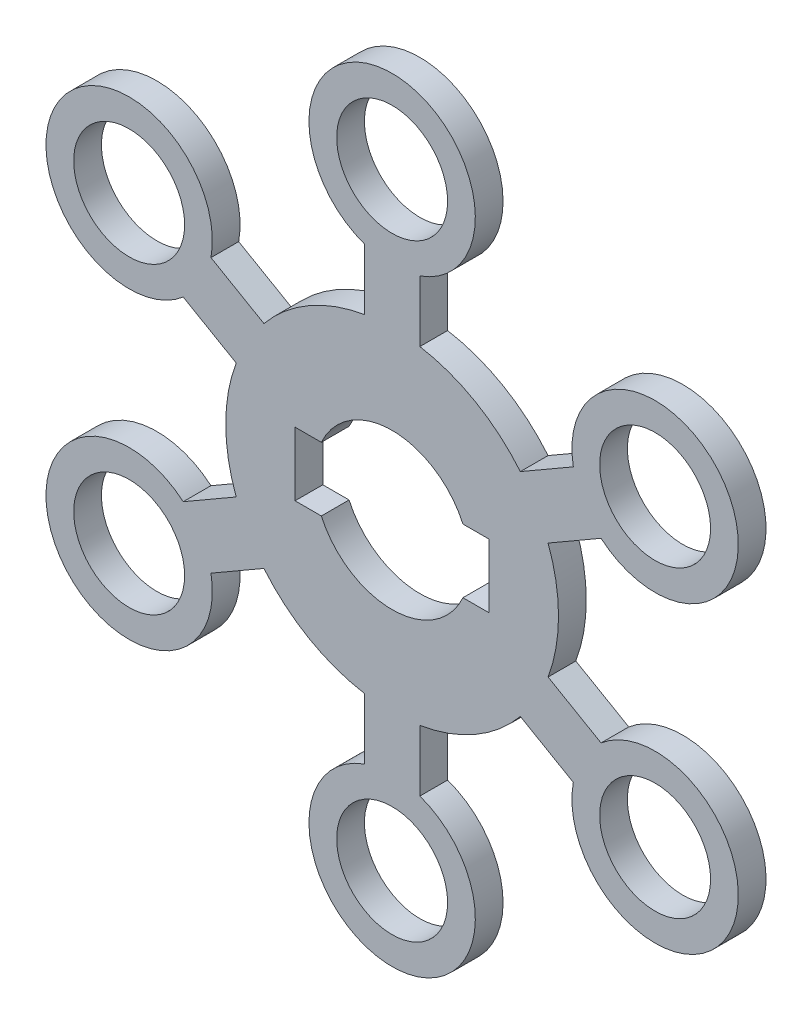
SolidWorks part; units mm, degrees
ref_plane "Front Plane" through (0, 0, 0) normal (0, 0, 1) x (1, 0, 0)
ref_plane "Top Plane" through (0, 0, 0) normal (0, 1, 0) x (1, 0, 0)
ref_plane "Right Plane" through (0, 0, 0) normal (1, 0, 0) x (0, 0, -1)
sketch "Sketch1" plane through (0, 0, 0) normal (0, 0, 1) x (1, 0, 0)
  line L0 (0, 167.3901) -> (0, -159.7467) construction
  line L1 (-233.5054, 0) -> (251.8495, 0) construction
  line L2 (-25.5294, 11.5) -> (-35, 11.5)
  line L3 (-35, 11.5) -> (-35, -11.5)
  line L4 (-35, -11.5) -> (-25.5294, -11.5)
  line L5 (35, -11.5) -> (25.5294, -11.5)
  line L6 (35, 11.5) -> (35, -11.5)
  line L7 (25.5294, 11.5) -> (35, 11.5)
  line L8 (0, 0) -> (94.8298, 54.75) construction
  line L9 (56.2348, 20.9201) -> (75.3349, 31.9476)
  line L10 (-5, 8.6603) -> (0, 11.547)
  line L11 (46.2348, 38.2407) -> (65.3349, 49.2681)
  line L12 (99.4335, 45.861) -> (99.8298, 46.0897)
  line L13 (-5, 8.6603) -> (89.8298, 63.4103) construction
  line L14 (5, -8.6603) -> (99.8298, 46.0897) construction
  line L15 (89.4335, 63.1815) -> (89.8298, 63.4103)
  line L16 (46.2348, -38.2407) -> (65.3349, -49.2681)
  line L17 (56.2348, -20.9201) -> (75.3349, -31.9476)
  line L18 (-10, -59.1608) -> (-10, -81.2157)
  line L19 (10, -59.1608) -> (10, -81.2157)
  line L20 (-56.2348, -20.9201) -> (-75.3349, -31.9476)
  line L21 (-46.2348, -38.2407) -> (-65.3349, -49.2681)
  line L22 (-46.2348, 38.2407) -> (-65.3349, 49.2681)
  line L23 (-56.2348, 20.9201) -> (-75.3349, 31.9476)
  line L24 (10, 59.1608) -> (10, 81.2157)
  line L25 (-10, 59.1608) -> (-10, 81.2157)
  arc A0 (-25.5294, -11.5) -> (25.5294, -11.5) centre (0, 0) ccw
  arc A1 (46.2348, 38.2407) -> (10, 59.1608) centre (0, 0) ccw
  circle A2 centre (0, 0) radius 109.5 construction
  arc A3 (25.5294, 11.5) -> (-25.5294, 11.5) centre (0, 0) ccw
  circle A4 centre (94.8298, 54.75) radius 20
  arc A5 (75.3349, 31.9476) -> (65.3349, 49.2681) centre (94.8298, 54.75) ccw
  arc A6 (65.3349, -49.2681) -> (75.3349, -31.9476) centre (94.8298, -54.75) ccw
  circle A7 centre (94.8298, -54.75) radius 20
  arc A8 (-10, -81.2157) -> (10, -81.2157) centre (0, -109.5) ccw
  circle A9 centre (0, -109.5) radius 20
  arc A10 (-75.3349, -31.9476) -> (-65.3349, -49.2681) centre (-94.8298, -54.75) ccw
  circle A11 centre (-94.8298, -54.75) radius 20
  arc A12 (-65.3349, 49.2681) -> (-75.3349, 31.9476) centre (-94.8298, 54.75) ccw
  circle A13 centre (-94.8298, 54.75) radius 20
  arc A14 (10, 81.2157) -> (-10, 81.2157) centre (0, 109.5) ccw
  circle A15 centre (0, 109.5) radius 20
  arc A16 (-56.2348, 20.9201) -> (-56.2348, -20.9201) centre (0, 0) ccw
  arc A17 (-10, 59.1608) -> (-46.2348, 38.2407) centre (0, 0) ccw
  arc A18 (-46.2348, -38.2407) -> (-10, -59.1608) centre (0, 0) ccw
  arc A19 (10, -59.1608) -> (46.2348, -38.2407) centre (0, 0) ccw
  arc A20 (56.2348, -20.9201) -> (56.2348, 20.9201) centre (0, 0) ccw
  point P60 (0, 0)
  dimension "D1" = 56
  dimension "D2" = 120
  dimension "D3" = 219
  dimension "D7" = 40
  dimension "D8" = 60
  dimension "D4" = 35
  dimension "D5" = 23
  dimension "D6" = 11.5
  dimension "D9" = 30
  dimension "D10" = 10
  dimension "D11" = 10
  dimension "D12" = 6
extrude "Boss-Extrude1" add sketch "Sketch1" along normal blind 10 contours L17 A20 L9 A5 L11 A1 L24 A14 L25 A17 L22 A12 L23 A16 L20 A10 L21 A18 L18 A8 L19 A19 L16 A6 A3 L7 L6 L5 A0 L4 L3 L2 A4 A7 A9 A11 A13 A15
